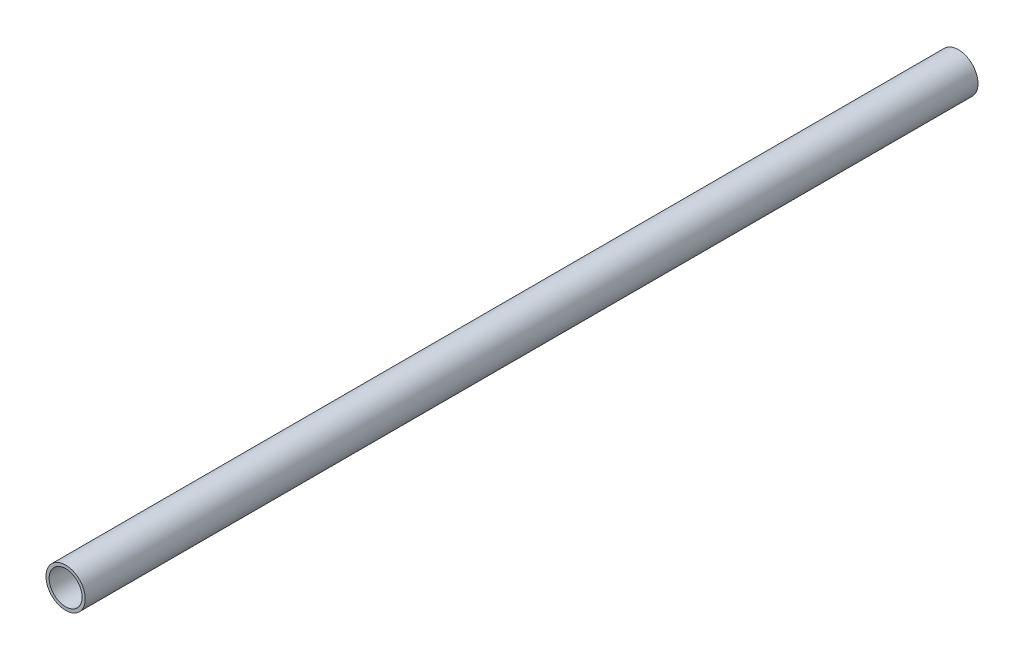
SolidWorks part; units mm, degrees
ref_plane "Alzado" through (0, 0, 0) normal (0, 0, 1) x (1, 0, 0)
ref_plane "Planta" through (0, 0, 0) normal (0, 1, 0) x (1, 0, 0)
ref_plane "Vista lateral" through (0, 0, 0) normal (1, 0, 0) x (0, 0, -1)
sketch "Croquis1" plane through (0, 0, 0) normal (0, 0, 1) x (1, 0, 0)
  circle A0 centre (0, 0) radius 12.5
  circle A1 centre (0, 0) radius 10.5
  dimension "D1" = 25
  dimension "D2" = 2
extrude "Saliente-Extruir1" add sketch "Croquis1" along normal blind 568
